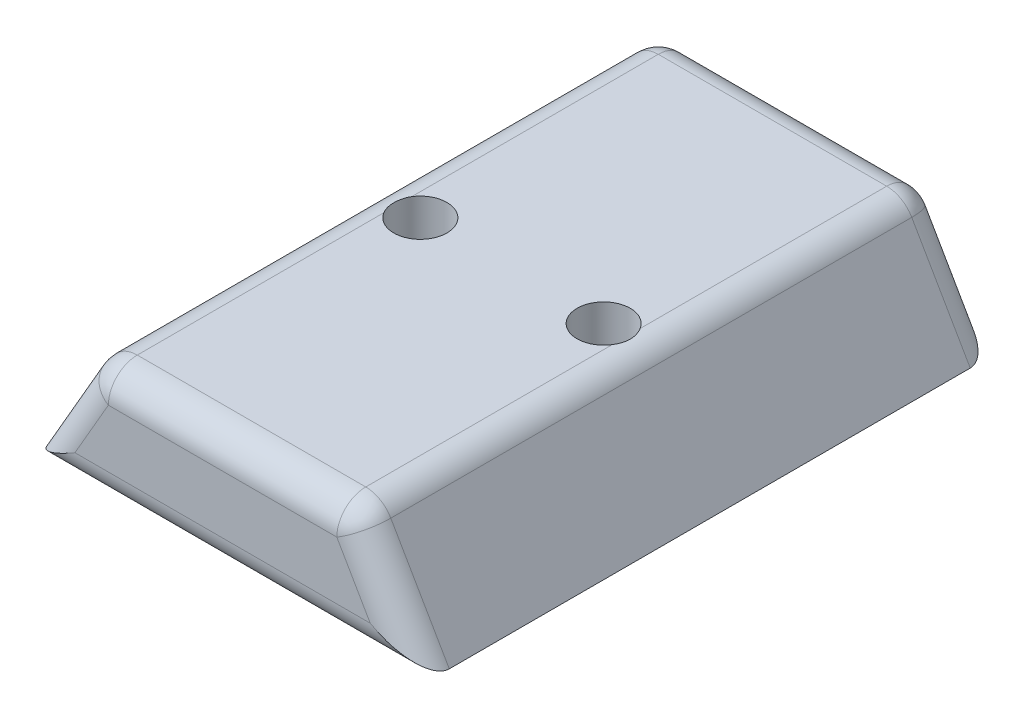
SolidWorks part; units mm, degrees
ref_plane "Front Plane" through (0, 0, 0) normal (0, 0, 1) x (1, 0, 0)
ref_plane "Top Plane" through (0, 0, 0) normal (0, 1, 0) x (1, 0, 0)
ref_plane "Right Plane" through (0, 0, 0) normal (1, 0, 0) x (0, 0, -1)
sketch "Sketch1" plane through (0, 0, 0) normal (0, 0, 1) x (1, 0, 0)
  line L0 (-20.5, 0) -> (-13.5718, 12)
  line L1 (-13.5718, 12) -> (13.5718, 12)
  line L2 (-20.5, 0) -> (20.5, 0)
  line L3 (0, 0) -> (0, 12) construction
  line L4 (20.5, 0) -> (13.5718, 12)
  dimension "D1" = 60
  dimension "D2" = 41
  dimension "D3" = 12
extrude "Boss-Extrude1" add sketch "Sketch1" along normal blind 60
fillet "Fillet1" radius 3 10 edges at (13.5718, 12, 30) (-13.5718, 12, 30) (-17.0359, 6, 60) (0, 12, 60) (17.0359, 6, 60) (0, 0, 60) (-17.0359, 6, 0) (0, 12, 0) (17.0359, 6, 0) (0, 0, 0)
sketch "Sketch3" plane through (0, 0, 0) normal (0, -1, 0) x (1, 0, 0)
  line L0 (-20.5, 57) -> (-20.5, 3) construction
  line L1 (-20.5, 30) -> (20.5, 30) construction
  line L2 (20.5, 57) -> (20.5, 3) construction
  line L3 (0, -6.6) -> (0, 6.6) construction
  circle A0 centre (-9.5, 30) radius 2.5
  circle A1 centre (9.5, 30) radius 2.5
  dimension "D1" = 5
  dimension "D2" = 11
hole_wizard "CBORE for M5 Hex Socket Head Cap Screw1" positions "Sketch4" profile "Sketch5" counterbore size "M5" standard "ISO" end condition through all
sketch "Sketch4" plane through (0, 0, 0) normal (0, -1, 0) x (-1, 0, 0)
  point P0 (-9.5, -30)
  point P3 (9.5, -30)
sketch "Sketch5" plane through (9.5, 0, 30) normal (1, 0, 0) x (0, 0, -1)
  line L0 (0, 0) -> (0, 12)
  line L1 (0, 12) -> (2.75, 12)
  line L3 (2.75, 12) -> (2.75, 5.4)
  line L4 (5, 5.4) -> (2.75, 5.4)
  line L5 (5, 5.4) -> (5, 0.025)
  line L6 (5, 0.025) -> (5.025, 0)
  line L7 (5.025, 0) -> (0, 0)
  line L8 (-5, 0.025) -> (-5.025, 0) construction
  line L11 (0, -6.35) -> (0, 107.95) construction
  dimension "Thru Hole Dia." = 5.5
  dimension "Thru Hole Depth" = 12
  dimension "C'Bore Dia." = 10
  dimension "C'Bore Depth" = 5.4
  dimension "Near C'Sink Dia." = 10.05
  dimension "Near C'Sink Angle" = 90
